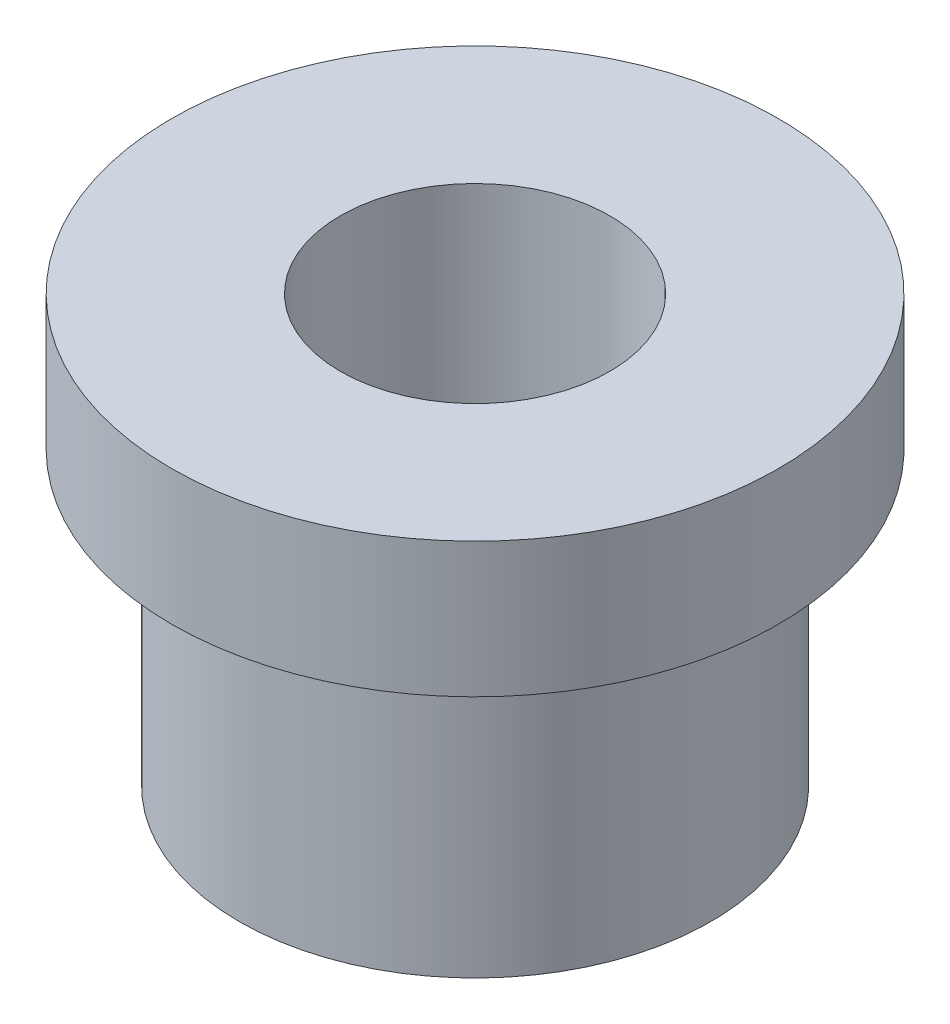
SolidWorks part; units mm, degrees
material "Brass"
ref_plane "Front Plane" through (0, 0, 0) normal (0, 0, 1) x (1, 0, 0)
ref_plane "Top Plane" through (0, 0, 0) normal (0, 1, 0) x (1, 0, 0)
ref_plane "Right Plane" through (0, 0, 0) normal (1, 0, 0) x (0, 0, -1)
sketch "Sketch1" plane through (0, 0, 0) normal (0, 1, 0) x (1, 0, 0)
  circle A0 centre (0, 0) radius 6.35
  circle A1 centre (0, 0) radius 11.1125
  dimension "D1" = 22.225
  dimension "D2" = 12.7
extrude "Boss-Extrude1" add sketch "Sketch1" along normal blind 13.716
sketch "Sketch2" plane through (0, 13.716, 0) normal (0, 1, 0) x (1, 0, 0)
  circle A0 centre (0, 0) radius 6.35
  circle A1 centre (0, 0) radius 14.2875
  dimension "D1" = 28.575
extrude "Boss-Extrude2" add sketch "Sketch2" along normal blind 6.35
